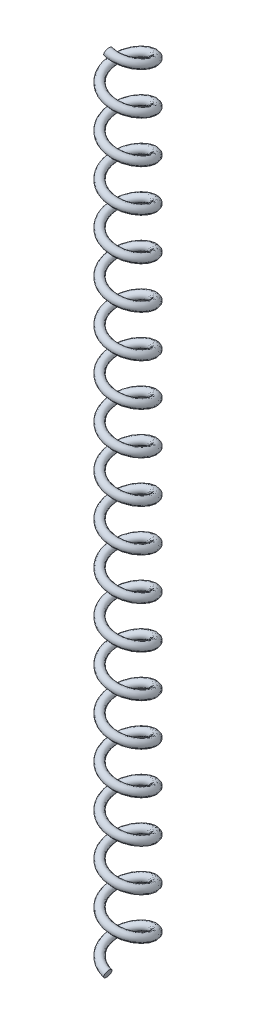
SolidWorks part; units mm, degrees
ref_plane "Front Plane" through (0, 0, 0) normal (0, 0, 1) x (1, 0, 0)
ref_plane "Top Plane" through (0, 0, 0) normal (0, 1, 0) x (1, 0, 0)
ref_plane "Right Plane" through (0, 0, 0) normal (1, 0, 0) x (0, 0, -1)
other "Configuration Table"
sketch "Sketch1" plane through (0, 0, 0) normal (0, 1, 0) x (1, 0, 0)
  circle A0 centre (0, 0) radius 1.25
curve "Coil_Helix" pitch 2.6053 height 49.5001 turns 19
sweep "Coil_Wire" add path "Coil_Helix" circular profile diameter 0.5 parameters "D3"=0.5
